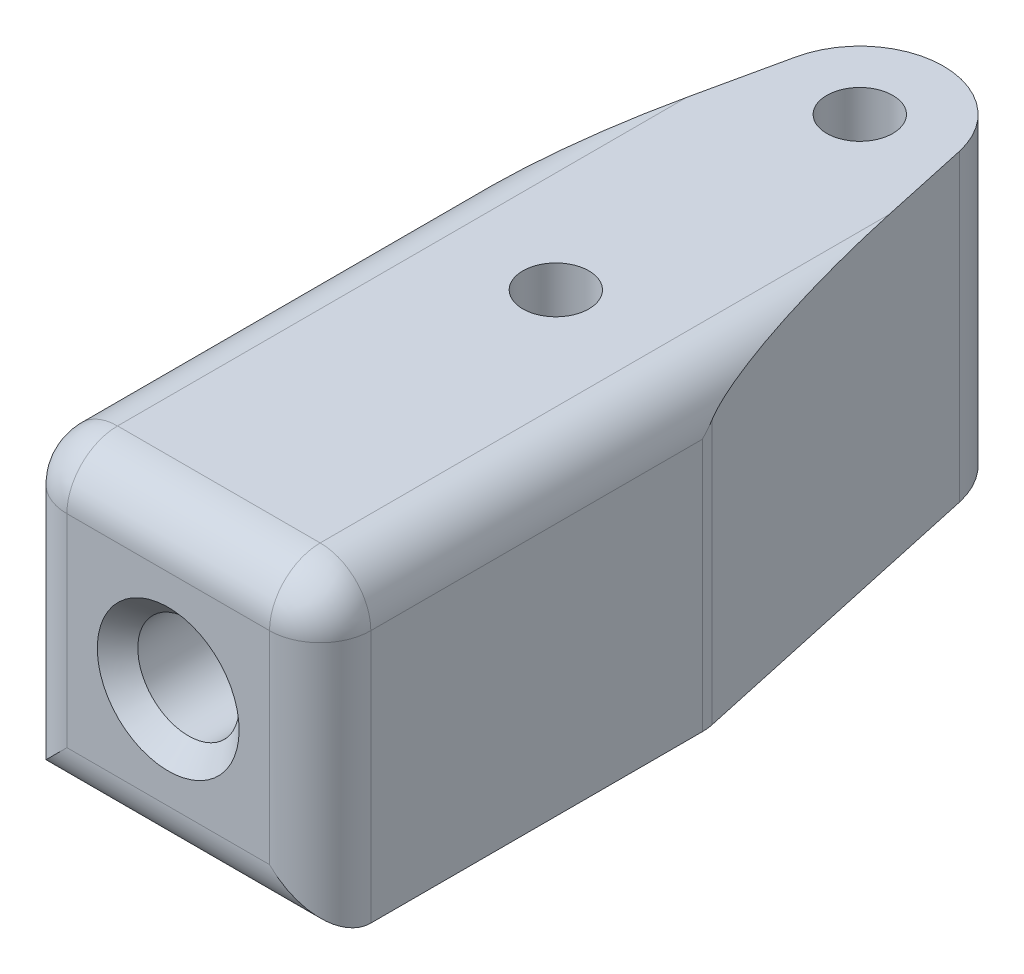
SolidWorks part; units mm, degrees
material "ABS"
ref_plane "Front Plane" through (0, 0, 0) normal (0, 0, 1) x (1, 0, 0)
ref_plane "Top Plane" through (0, 0, 0) normal (0, 1, 0) x (1, 0, 0)
ref_plane "Right Plane" through (0, 0, 0) normal (1, 0, 0) x (0, 0, -1)
sketch "Sketch2" plane through (0, 0, 0) normal (0, 1, 0) x (1, 0, 0)
  line L0 (0, 0) -> (0, -12536.8079) construction
  line L1 (9.525, 24.2951) -> (-9.525, 24.2951) construction
  line L2 (9.525, 24.2951) -> (9.525, -24.2951) construction
  line L3 (9.525, -24.2951) -> (-9.525, -24.2951)
  line L4 (-9.525, 24.2951) -> (-9.525, -24.2951) construction
  line L5 (9.525, 24.2951) -> (-9.525, -24.2951) construction
  line L6 (9.525, -24.2951) -> (-9.525, 24.2951) construction
  line L7 (0, 0) -> (-12536.8079, 0) construction
  line L8 (-9.525, 0) -> (-5.1245, 20.1681)
  line L9 (-3.175, -43.3451) -> (3.175, -43.3451)
  line L10 (-3.175, -43.3451) -> (-3.175, -5.2451) construction
  line L11 (-3.175, -5.2451) -> (3.175, -5.2451) construction
  line L12 (3.175, -43.3451) -> (3.175, -5.2451) construction
  line L13 (-3.175, -43.3451) -> (3.175, -5.2451) construction
  line L14 (-3.175, -5.2451) -> (3.175, -43.3451) construction
  line L15 (9.525, 0) -> (5.1245, 20.1681)
  line L16 (-9.525, -24.2951) -> (-9.525, 0)
  line L17 (9.525, -24.2951) -> (9.525, 0)
  circle A0 centre (0, 0) radius 2.0701
  circle A1 centre (0, 0) radius 5.2451 construction
  circle A2 centre (0, 19.05) radius 2.0701
  circle A3 centre (0, 19.05) radius 5.2451 construction
  arc A4 (5.1245, 20.1681) -> (-5.1245, 20.1681) centre (0, 19.05) ccw
  point P0 (0, 0)
  point P10 (0, -24.2951)
  dimension "D3" = 4.1402
  dimension "D4" = 3.175
  dimension "D1" = 6.35
  dimension "D2" = 19.05
  dimension "D5" = 19.05
  dimension "D6" = 19.05
extrude "Boss-Extrude1" add sketch "Sketch2" along normal blind 19.05 contours L15 A4 L8 L16 L3 L17
sketch "Sketch3" plane through (0, 0, 24.2951) normal (0, 0, 1) x (1, 0, 0)
  line L0 (0, 0) -> (0, 50000) construction
  line L1 (9.525, 9.525) -> (-49990.475, 9.525) construction
  line L2 (9.525, 19.05) -> (9.525, 0) construction
  circle A0 centre (0, 9.525) radius 3.175
  point P7 (9.525, 9.525)
  dimension "D1" = 6.35
extrude "Cut-Extrude1" cut sketch "Sketch3" against normal blind 19.05
chamfer "Chamfer1" distance 1.27 angle 45 1 edges at (3.175, 9.525, 24.2951)
fillet "Fillet1" radius 3.175 8 edges at (0, 0, 24.2951) (0, 19.05, 24.2951) (9.525, 9.525, 24.2951) (-9.525, 9.525, 24.2951) (-9.525, 9.525, 0) (9.525, 9.525, 0) (-9.525, 19.05, 12.1475) (9.525, 19.05, 12.1475)
